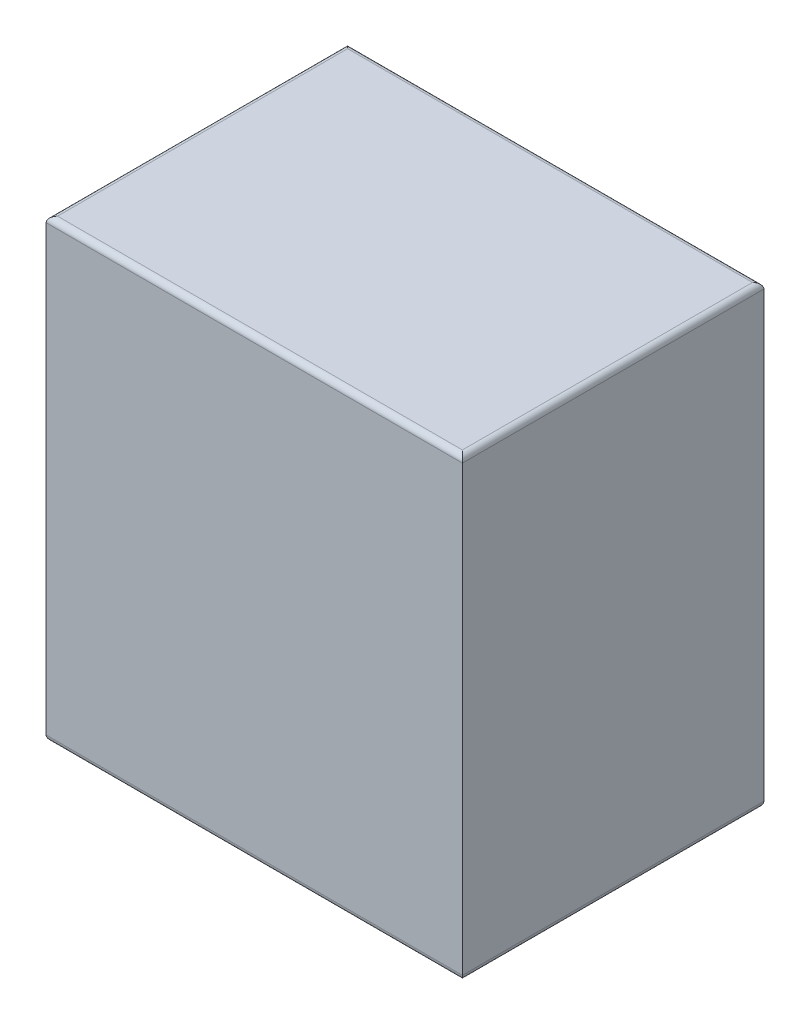
SolidWorks part; units mm, degrees
ref_plane "Front Plane" through (0, 0, 0) normal (1, 0, 0) x (0, 1, 0)
ref_plane "Top Plane" through (0, 0, 0) normal (0, 0, 1) x (0, 1, 0)
ref_plane "Right Plane" through (0, 0, 0) normal (0, 1, 0) x (-1, 0, 0)
sketch "Sketch1" plane through (0, 0, 0) normal (0, 1, 0) x (-1, 0, 0)
  line L0 (-0.4, -0.43) -> (-0.4, -26.93)
  line L1 (-0.4, -26.93) -> (-37, -26.93)
  line L2 (-37, -26.93) -> (-37, -0.43)
  line L3 (-37, -0.43) -> (-0.4, -0.43)
extrude "Boss-Extrude1" add sketch "Sketch1" along normal blind 40
fillet "Fillet1" radius 0.5 8 edges at (18.7, 0, -0.43) (37, 0, -13.68) (18.7, 0, -26.93) (0.4, 0, -13.68) (18.7, 40, -0.43) (37, 40, -13.68) (18.7, 40, -26.93) (0.4, 40, -13.68)
